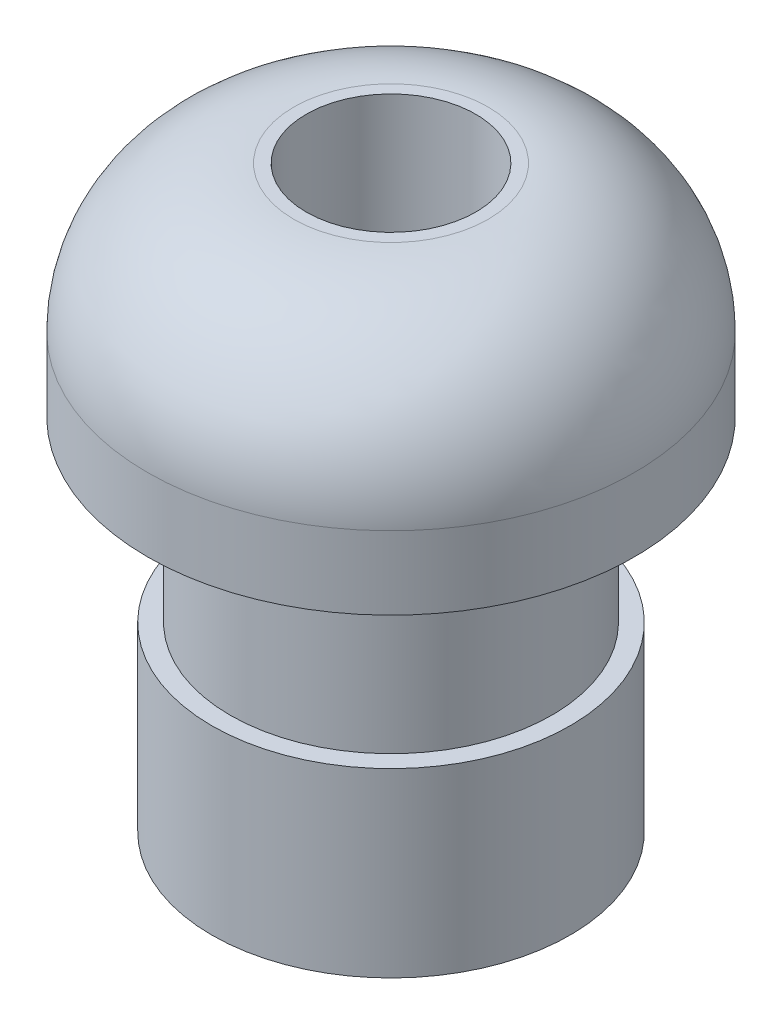
SolidWorks part; units mm, degrees
ref_plane "Front Plane" through (0, 0, 0) normal (0, 0, 1) x (1, 0, 0)
ref_plane "Top Plane" through (0, 0, 0) normal (0, 1, 0) x (1, 0, 0)
ref_plane "Right Plane" through (0, 0, 0) normal (1, 0, 0) x (0, 0, -1)
sketch "Sketch1" plane through (0, 0, 0) normal (0, 1, 0) x (1, 0, 0)
  line L0 (0, 8.9379) -> (0, -15.216) construction
  line L1 (-10.783, 0) -> (14.5691, 0) construction
  circle A0 centre (0, 0) radius 3.1115
  dimension "D1" = 6.223
extrude "Boss-Extrude1" add sketch "Sketch1" along normal blind 3.1496
sketch "Sketch3" plane through (0, 3.1496, 0) normal (0, 1, 0) x (1, 0, 0)
  line L0 (0, 3.4266) -> (0, -3.558) construction
  line L1 (4.8389, 0) -> (-5.1308, 0) construction
  circle A0 centre (0, 0) radius 2.794
  dimension "D1" = 5.588
extrude "Boss-Extrude2" add sketch "Sketch3" along normal blind 3.0988
sketch "Sketch4" plane through (0, 6.2484, 0) normal (0, 1, 0) x (1, 0, 0)
  line L0 (0, 3.3171) -> (0, -3.6237) construction
  line L1 (-5.3133, 0) -> (4.8097, 0) construction
  circle A0 centre (0, 0) radius 4.2291
  dimension "D1" = 8.4582
extrude "Boss-Extrude3" add sketch "Sketch4" along normal blind 3.81
sketch "Sketch5" plane through (0, 10.0584, 0) normal (0, 1, 0) x (1, 0, 0)
  circle A0 centre (0, 0) radius 1.4732
  dimension "D1" = 2.9464
extrude "Cut-Extrude1" cut sketch "Sketch5" against normal through all both and the other way through all
fillet "Fillet1" radius 2.54 1 edges at (0, 10.0584, 4.2291)
